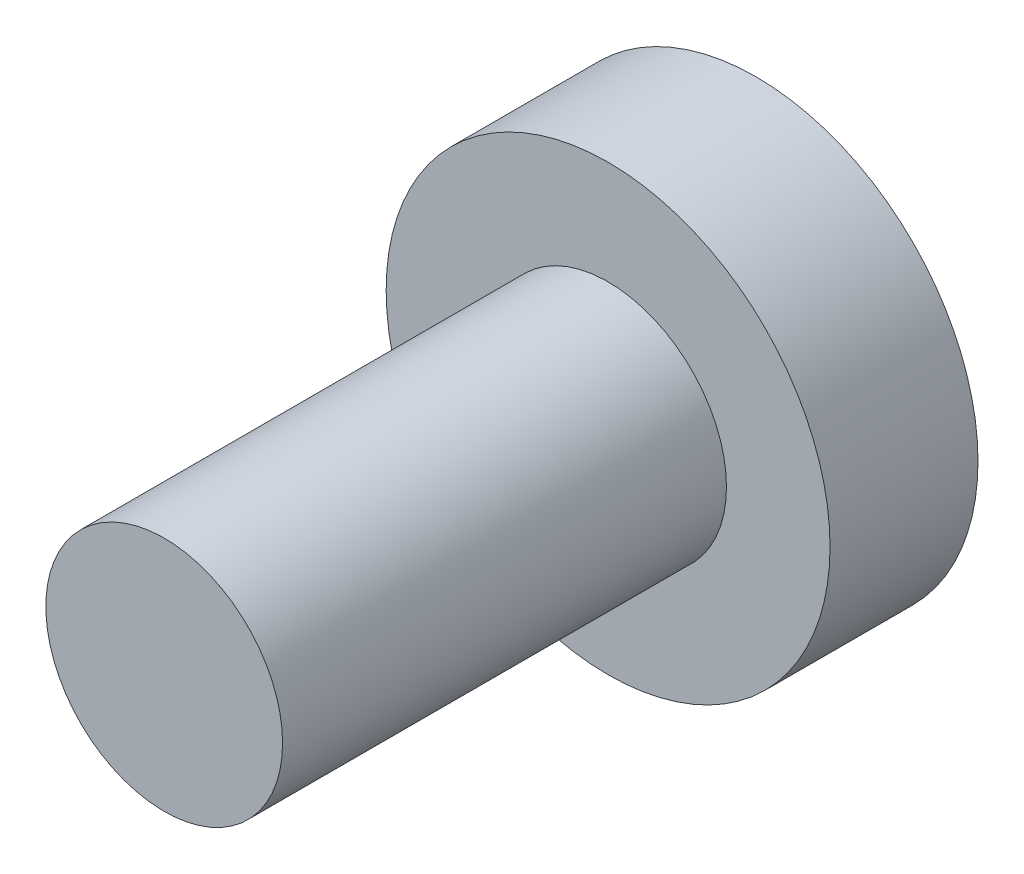
SolidWorks part; units mm, degrees
material "AISI 304"
ref_plane "Alzado" through (0, 0, 0) normal (0, 0, 1) x (1, 0, 0)
ref_plane "Planta" through (0, 0, 0) normal (0, 1, 0) x (1, 0, 0)
ref_plane "Vista lateral" through (0, 0, 0) normal (1, 0, 0) x (0, 0, -1)
sketch "Sk_Cabeza_avellanada" plane through (0, 0, 0) normal (0, 0, 1) x (1, 0, 0)
  circle A0 centre (0, 0) radius 3.75
  dimension "D1" = 7.5
extrude "Cabeza_avellanada" add sketch "Sk_Cabeza_avellanada" along normal blind 2.5
sketch "Sk_Cuerpo" plane through (0, 0, 0) normal (0, 0, 1) x (1, 0, 0)
  circle A0 centre (0, 0) radius 2
  dimension "D1" = 4
extrude "Cuerpo" add sketch "Sk_Cuerpo" along normal blind 10
sketch "Sk_Hexagono_interior" plane through (0, 0, 0) normal (0, 0, 1) x (1, 0, 0)
  line L1 (0, -1.4434) -> (1.25, -0.7217)
  line L2 (1.25, -0.7217) -> (1.25, 0.7217)
  line L3 (1.25, 0.7217) -> (0, 1.4434)
  line L4 (0, 1.4434) -> (-1.25, 0.7217)
  line L5 (-1.25, 0.7217) -> (-1.25, -0.7217)
  line L6 (-1.25, -0.7217) -> (0, -1.4434)
  circle A0 centre (0, 0) radius 1.25 construction
  dimension "D1" = 2.5
extrude "Hexagono_interior" cut sketch "Sk_Hexagono_interior" along normal blind 1.5
